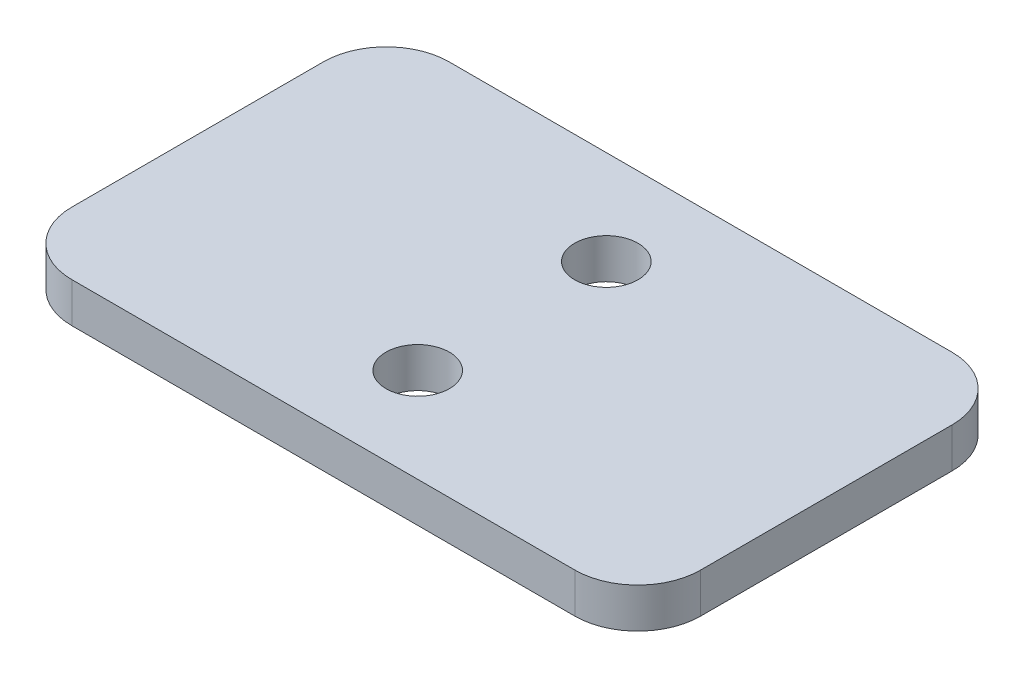
SolidWorks part; units mm, degrees
ref_plane "Front Plane" through (0, 0, 0) normal (0, 0, 1) x (1, 0, 0)
ref_plane "Top Plane" through (0, 0, 0) normal (0, 1, 0) x (1, 0, 0)
ref_plane "Right Plane" through (0, 0, 0) normal (1, 0, 0) x (0, 0, -1)
sketch "Sketch1" plane through (0, 0, 0) normal (0, 1, 0) x (1, 0, 0)
  line L1 (-50, -30) -> (50, -30)
  line L2 (-50, -30) -> (-50, 30)
  line L3 (-50, 30) -> (50, 30)
  line L4 (50, -30) -> (50, 30)
  line L5 (-50, -30) -> (50, 30) construction
  line L6 (-50, 30) -> (50, -30) construction
  point P0 (0, 0)
  dimension "D1" = 100
  dimension "D2" = 60
extrude "Boss-Extrude1" add sketch "Sketch1" along normal blind 6.35 contours L4 L3 L2 L1
sketch "Sketch2" plane through (0, 6.35, 0) normal (0, 1, 0) x (1, 0, 0)
  line L0 (0, 15) -> (0, -15) construction
  line L2 (-50, -30) -> (-50, 30) construction
  point P3 (0, 0)
  point P4 (0, 0)
  point P7 (-50, 0)
  dimension "D1" = 30
hole_wizard "3/8 Clearance Hole1" positions "Sketch3" profile "Sketch5" hole size "3/8" standard "ANSI Inch" end condition through all
sketch "Sketch3" plane through (0, 6.35, 0) normal (0, 1, 0) x (1, 0, 0)
  point P0 (0, 15)
  point P3 (0, -15)
sketch "Sketch5" plane through (0, 6.35, -15) normal (1, 0, 0) x (0, 0, 1)
  line L0 (0, 0) -> (0, 6.35)
  line L1 (0, 6.35) -> (5.0419, 6.35)
  line L2 (5.0419, 6.35) -> (5.0419, 0)
  line L5 (5.0419, 0) -> (0, 0)
  line L11 (0, -6.35) -> (0, 107.95) construction
  dimension "Thru Hole Dia." = 10.0838
  dimension "Thru Hole Depth" = 6.35
fillet "Fillet1" radius 10 4 edges at (-50, 3.175, -30) (-50, 3.175, 30) (50, 3.175, -30) (50, 3.175, 30)
